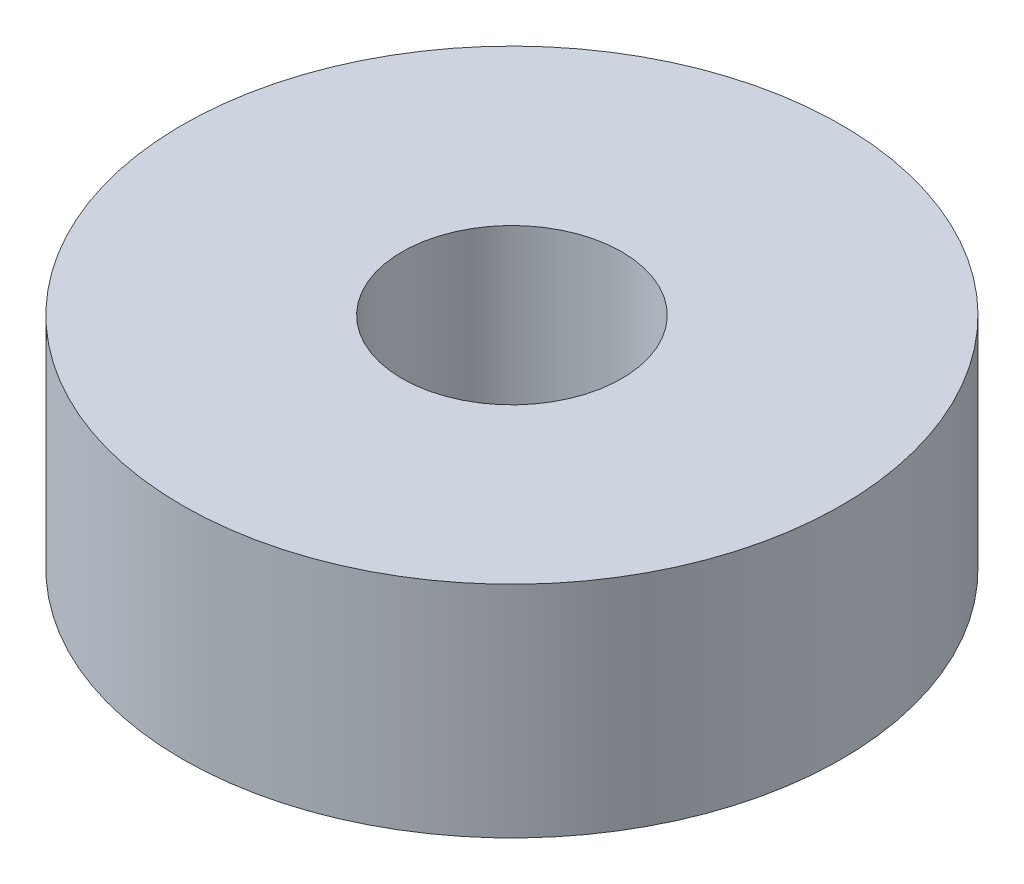
SolidWorks part; units mm, degrees
ref_plane "Front Plane" through (0, 0, 0) normal (0, 0, 1) x (1, 0, 0)
ref_plane "Top Plane" through (0, 0, 0) normal (0, 1, 0) x (1, 0, 0)
ref_plane "Right Plane" through (0, 0, 0) normal (1, 0, 0) x (0, 0, -1)
sketch "Sketch1" plane through (0, 0, 0) normal (0, 1, 0) x (1, 0, 0)
  circle A0 centre (0, 0) radius 15
  circle A1 centre (0, 0) radius 5
  dimension "D1" = 30
  dimension "D2" = 10
extrude "Boss-Extrude1" add sketch "Sketch1" along normal blind 10
